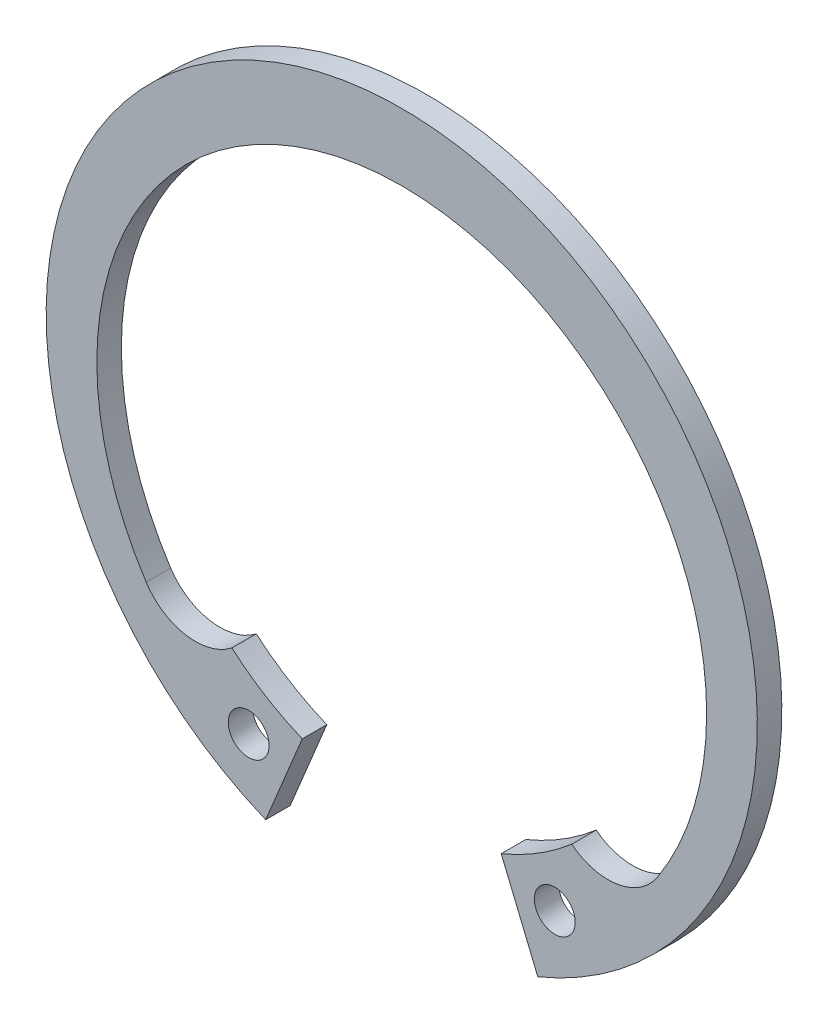
SolidWorks part; units mm, degrees
ref_plane "Front" through (0, 0, 0) normal (0, 0, 1) x (1, 0, 0)
ref_plane "Top" through (0, 0, 0) normal (0, 1, 0) x (1, 0, 0)
ref_plane "Right" through (0, 0, 0) normal (1, 0, 0) x (0, 0, -1)
sketch "Sketch1" plane through (0, 0, 0) normal (0, 0, 1) x (1, 0, 0)
  line L0 (-6.0847, -14.6897) -> (-8.3234, -20.0944)
  line L1 (6.0847, -14.6897) -> (8.3234, -20.0944)
  line L2 (0, 17.9027) -> (0, -23.5886) construction
  arc A0 (8.3234, -20.0944) -> (-8.3234, -20.0944) centre (0, 0) ccw
  arc A1 (15.6383, -11.162) -> (-15.6383, -11.162) centre (0, -1) ccw
  arc A2 (7.1179, -17.1842) -> (-7.1179, -17.1842) centre (0, 0) ccw construction
  circle A3 centre (9.363, -16.0715) radius 1.25
  arc A4 (-15.6383, -11.162) -> (-10.3954, -12.031) centre (-12.6197, -9.2004) ccw
  arc A5 (-10.3954, -12.031) -> (-6.0847, -14.6897) centre (0, 0) ccw
  circle A6 centre (-9.363, -16.0715) radius 1.25
  arc A8 (10.3954, -12.031) -> (6.0847, -14.6897) centre (0, 0) cw
  arc A9 (15.6383, -11.162) -> (10.3954, -12.031) centre (12.6197, -9.2004) cw
  dimension "R2" = 3.6
  dimension "d1" = 2.5
  dimension "d0" = 37.3
  dimension "D" = 43.5
  dimension "R" = 18.6
  dimension "a" = 5.85
  dimension "c" = 1
  dimension "Angle" = 45
  dimension "B" = 5
  dimension "B1" = 2.5
extrude "Body" add sketch "Sketch1" against normal blind 1.5
